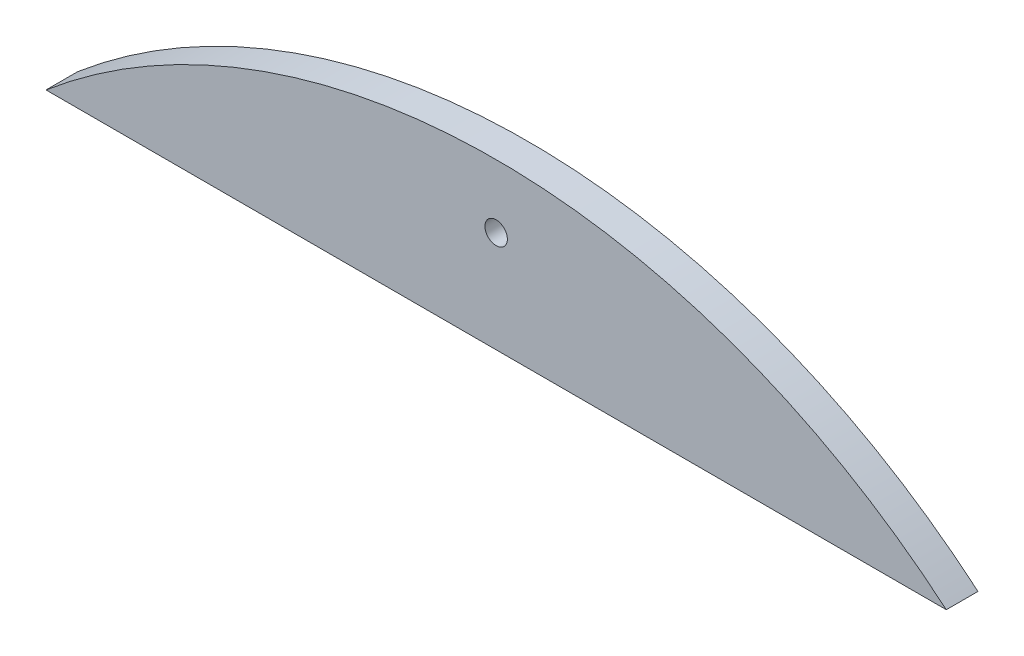
SolidWorks part; units mm, degrees
material "Copper"
ref_plane "Front Plane" through (0, 0, 0) normal (0, 0, 1) x (1, 0, 0)
ref_plane "Top Plane" through (0, 0, 0) normal (0, 1, 0) x (1, 0, 0)
ref_plane "Right Plane" through (0, 0, 0) normal (1, 0, 0) x (0, 0, -1)
sketch "Sketch1" plane through (0, 0, 0) normal (0, 0, 1) x (1, 0, 0)
  line L0 (-90.1968, 106.68) -> (90.1968, 106.68)
  line L1 (55, 0) -> (-55, 0) construction
  circle A0 centre (0, 0) radius 139.7
  dimension "D1" = 279.4
  dimension "D2" = 106.68
  dimension "D3" = 0
extrude "Boss-Extrude1" add sketch "Sketch1" along normal blind 6.35 contours L0 A0
hole_wizard "#8 Clearance Hole1" positions "Sketch2" profile "Sketch3" hole size "#8" standard "ANSI Inch" end condition through all
sketch "Sketch2" plane through (0, 0, 6.35) normal (0, 0, 1) x (1, 0, 0)
  point P0 (0, 127)
  dimension "D1" = 127
sketch "Sketch3" plane through (0, 127, 6.35) normal (1, 0, 0) x (0, -1, 0)
  line L0 (0, 0) -> (0, 6.35)
  line L1 (0, 6.35) -> (2.2479, 6.35)
  line L2 (2.2479, 6.35) -> (2.2479, 0)
  line L5 (2.2479, 0) -> (0, 0)
  line L11 (0, -6.35) -> (0, 107.95) construction
  dimension "Thru Hole Dia." = 4.4958
  dimension "Thru Hole Depth" = 6.35
